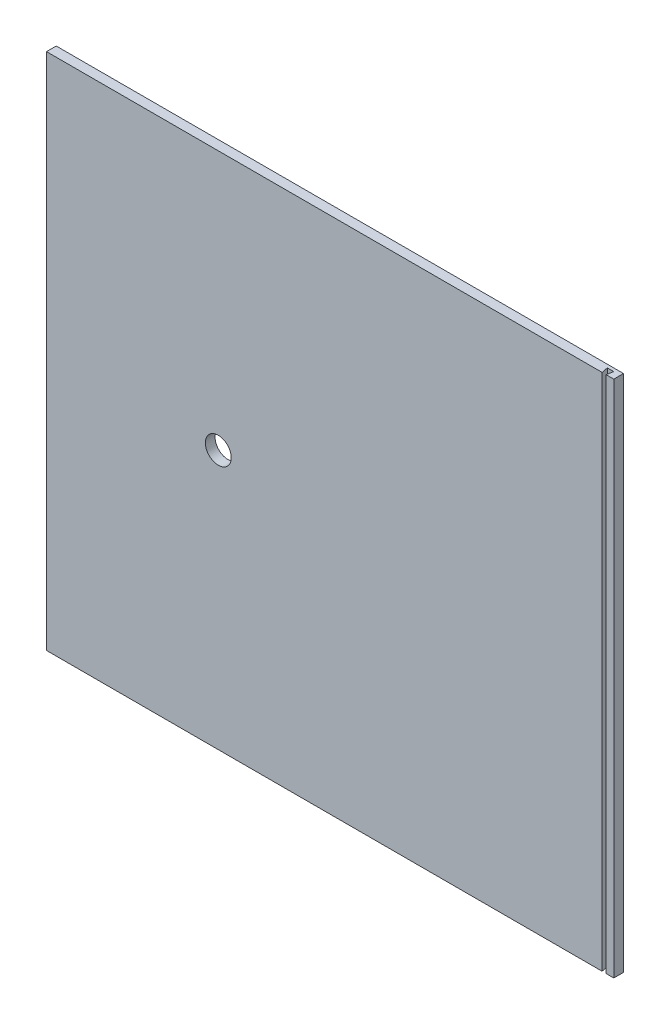
SolidWorks part; units mm, degrees
ref_plane "Front Plane" through (0, 0, 0) normal (0, 0, 1) x (1, 0, 0)
ref_plane "Top Plane" through (0, 0, 0) normal (0, 1, 0) x (1, 0, 0)
ref_plane "Right Plane" through (0, 0, 0) normal (1, 0, 0) x (0, 0, -1)
sketch "Sketch1" plane through (0, 0, 0) normal (0, 0, 1) x (1, 0, 0)
  line L1 (0, 0) -> (87.5, 0)
  line L2 (0, 0) -> (0, 80)
  line L3 (0, 80) -> (87.5, 80)
  line L4 (87.5, 0) -> (87.5, 80)
  dimension "D1" = 80
  dimension "D2" = 87.5
extrude "Boss-Extrude1" add sketch "Sketch1" along normal blind 1.5
sketch "Sketch2" plane through (0, 80, 0) normal (0, 1, 0) x (1, 0, 0)
  line L1 (85.5, -0.4929) -> (85.5, -1.5) construction
  line L5 (85.5, -1.5) -> (85.7, -1.5)
  line L17 (85.5, -0.4929) -> (85.7, -1.5)
  line L20 (85.5, -0.4929) -> (86.5, -0.4929)
  line L21 (86, -0.4929) -> (86, -1.5) construction
  line L24 (85.7, -1.5) -> (86.3, -1.5)
  line L27 (86.5, -0.4929) -> (87.5, -0.4929) construction
  line L28 (87.5, -1.5) -> (87.5, 0) construction
  line L29 (86.5, -0.4929) -> (86.3, -1.5)
  line M7 (0, -1.5) -> (87.5, -1.5)
  dimension "D1" = 1
extrude "Cut-Extrude1" cut sketch "Sketch2" against normal up to surface (80 mm away) contours L29 L20 L17 M7 up to face at (43.75, 0, 0.75)
sketch "Sketch3" plane through (0, 0, 0) normal (0, 0, -1) x (-1, 0, 0)
  circle A1 centre (-26.5, 40) radius 2
extrude "Cut-Extrude2" cut sketch "Sketch3" against normal up to surface (1.5 mm away) up to face at (42.85, 40, 1.5)
